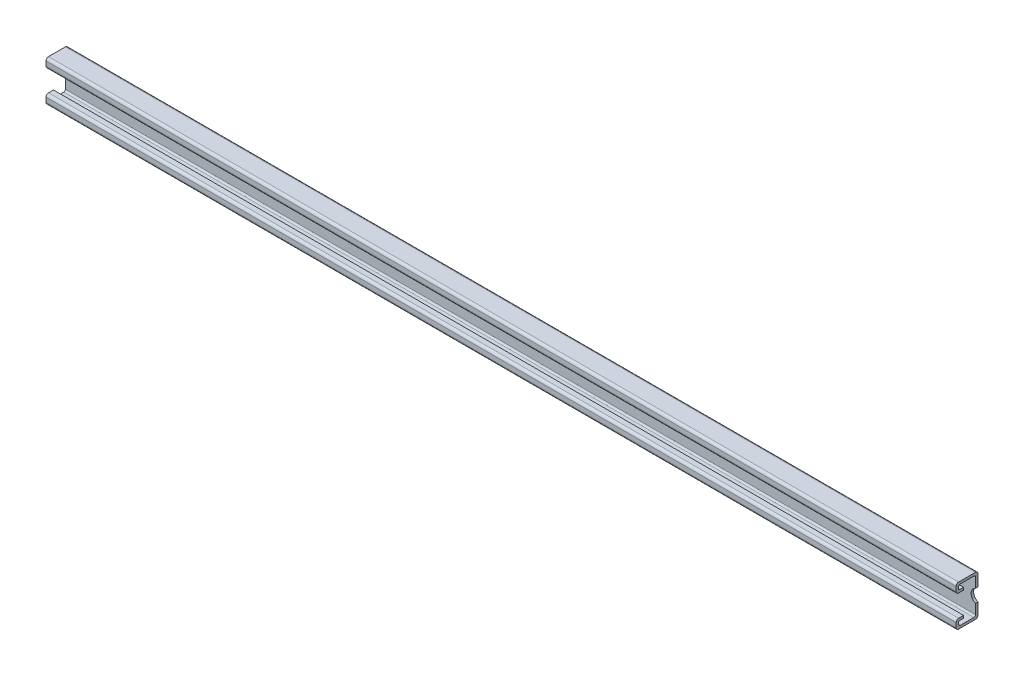
SolidWorks part; units mm, degrees
ref_plane "Front Plane" through (0, 0, 0) normal (0, 0, 1) x (1, 0, 0)
ref_plane "Top Plane" through (0, 0, 0) normal (0, 1, 0) x (1, 0, 0)
ref_plane "Right Plane" through (0, 0, 0) normal (1, 0, 0) x (0, 0, -1)
ref_plane "Plane1" through (0, 0, -11) normal (0, 0, -1) x (-1, 0, 0)
sketch "Sketch1" plane through (0, 0, -11) normal (0, 0, -1) x (-1, 0, 0)
  line L0 (0, 0) -> (0, 41)
  line L1 (0, 41) -> (-1000, 41)
  line L2 (-1000, 41) -> (-1000, 0)
  line L3 (-1000, 0) -> (0, 0)
extrude "Boss-Extrude1" add sketch "Sketch1" against normal blind 22
sketch "Sketch2" plane through (1000, 0, 0) normal (1, 0, 0) x (0, 0, -1)
  line L0 (-11, 9.5) -> (-3.5, 9.5)
  line L1 (-3.5, 9.5) -> (-3.5, 7)
  line L2 (-3.5, 7) -> (-8.5, 7)
  line L3 (-8.5, 7) -> (-8.5, 2.5)
  line L4 (-8.5, 2.5) -> (8.5, 2.5)
  line L5 (8.5, 2.5) -> (8.5, 38.5)
  line L6 (8.5, 38.5) -> (-8.5, 38.5)
  line L7 (-8.5, 38.5) -> (-8.5, 31.5)
  line L8 (-8.5, 31.5) -> (-11, 31.5)
  line L9 (-11, 31.5) -> (-11, 9.5)
extrude "Cut-Extrude1" cut sketch "Sketch2" against normal through all
sketch "Sketch3" plane through (0, 0, 8.5) normal (0, 0, -1) x (-1, 0, 0)
  line L0 (0, 34) -> (0, 31.5)
  line L1 (0, 31.5) -> (-1000, 31.5)
  line L2 (-1000, 31.5) -> (-1000, 34)
  line L3 (-1000, 34) -> (0, 34)
extrude "Boss-Extrude2" add sketch "Sketch3" along normal blind 5
sketch "Sketch4" plane through (0, 0, -11) normal (0, 0, -1) x (-1, 0, 0)
  line L0 (-117, 27.5) -> (-133, 27.5)
  line L1 (-133, 13.5) -> (-117, 13.5)
  arc A0 (-133, 27.5) -> (-133, 13.5) centre (-133, 20.5) ccw
  arc A1 (-117, 13.5) -> (-117, 27.5) centre (-117, 20.5) ccw
extrude "Cut-Extrude2" cut sketch "Sketch4" against normal through all
sketch "Sketch5" plane through (0, 0, -11) normal (0, 0, -1) x (-1, 0, 0)
  line L0 (-217, 27.5) -> (-233, 27.5)
  line L1 (-233, 13.5) -> (-217, 13.5)
  arc A0 (-233, 27.5) -> (-233, 13.5) centre (-233, 20.5) ccw
  arc A1 (-217, 13.5) -> (-217, 27.5) centre (-217, 20.5) ccw
extrude "Cut-Extrude3" cut sketch "Sketch5" against normal through all
sketch "Sketch6" plane through (0, 0, -11) normal (0, 0, -1) x (-1, 0, 0)
  line L0 (-317, 27.5) -> (-333, 27.5)
  line L1 (-333, 13.5) -> (-317, 13.5)
  arc A0 (-333, 27.5) -> (-333, 13.5) centre (-333, 20.5) ccw
  arc A1 (-317, 13.5) -> (-317, 27.5) centre (-317, 20.5) ccw
extrude "Cut-Extrude4" cut sketch "Sketch6" against normal through all
sketch "Sketch7" plane through (0, 0, -11) normal (0, 0, -1) x (-1, 0, 0)
  line L0 (-417, 27.5) -> (-433, 27.5)
  line L1 (-433, 13.5) -> (-417, 13.5)
  arc A0 (-433, 27.5) -> (-433, 13.5) centre (-433, 20.5) ccw
  arc A1 (-417, 13.5) -> (-417, 27.5) centre (-417, 20.5) ccw
extrude "Cut-Extrude5" cut sketch "Sketch7" against normal through all
sketch "Sketch8" plane through (0, 0, -11) normal (0, 0, -1) x (-1, 0, 0)
  line L0 (-517, 27.5) -> (-533, 27.5)
  line L1 (-533, 13.5) -> (-517, 13.5)
  arc A0 (-533, 27.5) -> (-533, 13.5) centre (-533, 20.5) ccw
  arc A1 (-517, 13.5) -> (-517, 27.5) centre (-517, 20.5) ccw
extrude "Cut-Extrude6" cut sketch "Sketch8" against normal through all
sketch "Sketch9" plane through (0, 0, -11) normal (0, 0, -1) x (-1, 0, 0)
  line L0 (-617, 27.5) -> (-633, 27.5)
  line L1 (-633, 13.5) -> (-617, 13.5)
  arc A0 (-633, 27.5) -> (-633, 13.5) centre (-633, 20.5) ccw
  arc A1 (-617, 13.5) -> (-617, 27.5) centre (-617, 20.5) ccw
extrude "Cut-Extrude7" cut sketch "Sketch9" against normal through all
sketch "Sketch10" plane through (0, 0, -11) normal (0, 0, -1) x (-1, 0, 0)
  line L0 (-717, 27.5) -> (-733, 27.5)
  line L1 (-733, 13.5) -> (-717, 13.5)
  arc A0 (-733, 27.5) -> (-733, 13.5) centre (-733, 20.5) ccw
  arc A1 (-717, 13.5) -> (-717, 27.5) centre (-717, 20.5) ccw
extrude "Cut-Extrude8" cut sketch "Sketch10" against normal through all
sketch "Sketch11" plane through (0, 0, -11) normal (0, 0, -1) x (-1, 0, 0)
  line L0 (-817, 27.5) -> (-833, 27.5)
  line L1 (-833, 13.5) -> (-817, 13.5)
  arc A0 (-833, 27.5) -> (-833, 13.5) centre (-833, 20.5) ccw
  arc A1 (-817, 13.5) -> (-817, 27.5) centre (-817, 20.5) ccw
extrude "Cut-Extrude9" cut sketch "Sketch11" against normal through all
sketch "Sketch12" plane through (0, 0, -11) normal (0, 0, -1) x (-1, 0, 0)
  line L0 (-917, 27.5) -> (-933, 27.5)
  line L1 (-933, 13.5) -> (-917, 13.5)
  arc A0 (-933, 27.5) -> (-933, 13.5) centre (-933, 20.5) ccw
  arc A1 (-917, 13.5) -> (-917, 27.5) centre (-917, 20.5) ccw
extrude "Cut-Extrude10" cut sketch "Sketch12" against normal through all
sketch "Sketch13" plane through (0, 0, -11) normal (0, 0, -1) x (-1, 0, 0)
  line L0 (-17, 27.5) -> (-33, 27.5)
  line L1 (-33, 13.5) -> (-17, 13.5)
  arc A0 (-33, 27.5) -> (-33, 13.5) centre (-33, 20.5) ccw
  arc A1 (-17, 13.5) -> (-17, 27.5) centre (-17, 20.5) ccw
extrude "Cut-Extrude11" cut sketch "Sketch13" against normal through all
sketch "Sketch14" plane through (0, 0, -11) normal (0, 0, -1) x (-1, 0, 0)
  line L0 (-967, 27.5) -> (-983, 27.5)
  line L1 (-983, 13.5) -> (-967, 13.5)
  arc A0 (-983, 27.5) -> (-983, 13.5) centre (-983, 20.5) ccw
  arc A1 (-967, 13.5) -> (-967, 27.5) centre (-967, 20.5) ccw
extrude "Cut-Extrude12" cut sketch "Sketch14" against normal through all
sketch "Sketch15" plane through (0, 0, -11) normal (0, 0, -1) x (-1, 0, 0)
  line L0 (-867, 27.5) -> (-883, 27.5)
  line L1 (-883, 13.5) -> (-867, 13.5)
  arc A0 (-883, 27.5) -> (-883, 13.5) centre (-883, 20.5) ccw
  arc A1 (-867, 13.5) -> (-867, 27.5) centre (-867, 20.5) ccw
extrude "Cut-Extrude13" cut sketch "Sketch15" against normal through all
sketch "Sketch16" plane through (0, 0, -11) normal (0, 0, -1) x (-1, 0, 0)
  line L0 (-767, 27.5) -> (-783, 27.5)
  line L1 (-783, 13.5) -> (-767, 13.5)
  arc A0 (-783, 27.5) -> (-783, 13.5) centre (-783, 20.5) ccw
  arc A1 (-767, 13.5) -> (-767, 27.5) centre (-767, 20.5) ccw
extrude "Cut-Extrude14" cut sketch "Sketch16" against normal through all
sketch "Sketch17" plane through (0, 0, -11) normal (0, 0, -1) x (-1, 0, 0)
  line L0 (-667, 27.5) -> (-683, 27.5)
  line L1 (-683, 13.5) -> (-667, 13.5)
  arc A0 (-683, 27.5) -> (-683, 13.5) centre (-683, 20.5) ccw
  arc A1 (-667, 13.5) -> (-667, 27.5) centre (-667, 20.5) ccw
extrude "Cut-Extrude15" cut sketch "Sketch17" against normal through all
sketch "Sketch18" plane through (0, 0, -11) normal (0, 0, -1) x (-1, 0, 0)
  line L0 (-567, 27.5) -> (-583, 27.5)
  line L1 (-583, 13.5) -> (-567, 13.5)
  arc A0 (-583, 27.5) -> (-583, 13.5) centre (-583, 20.5) ccw
  arc A1 (-567, 13.5) -> (-567, 27.5) centre (-567, 20.5) ccw
extrude "Cut-Extrude16" cut sketch "Sketch18" against normal through all
sketch "Sketch19" plane through (0, 0, -11) normal (0, 0, -1) x (-1, 0, 0)
  line L0 (-467, 27.5) -> (-483, 27.5)
  line L1 (-483, 13.5) -> (-467, 13.5)
  arc A0 (-483, 27.5) -> (-483, 13.5) centre (-483, 20.5) ccw
  arc A1 (-467, 13.5) -> (-467, 27.5) centre (-467, 20.5) ccw
extrude "Cut-Extrude17" cut sketch "Sketch19" against normal through all
sketch "Sketch20" plane through (0, 0, -11) normal (0, 0, -1) x (-1, 0, 0)
  line L0 (-367, 27.5) -> (-383, 27.5)
  line L1 (-383, 13.5) -> (-367, 13.5)
  arc A0 (-383, 27.5) -> (-383, 13.5) centre (-383, 20.5) ccw
  arc A1 (-367, 13.5) -> (-367, 27.5) centre (-367, 20.5) ccw
extrude "Cut-Extrude18" cut sketch "Sketch20" against normal through all
sketch "Sketch21" plane through (0, 0, -11) normal (0, 0, -1) x (-1, 0, 0)
  line L0 (-267, 27.5) -> (-283, 27.5)
  line L1 (-283, 13.5) -> (-267, 13.5)
  arc A0 (-283, 27.5) -> (-283, 13.5) centre (-283, 20.5) ccw
  arc A1 (-267, 13.5) -> (-267, 27.5) centre (-267, 20.5) ccw
extrude "Cut-Extrude19" cut sketch "Sketch21" against normal through all
sketch "Sketch22" plane through (0, 0, -11) normal (0, 0, -1) x (-1, 0, 0)
  line L0 (-167, 27.5) -> (-183, 27.5)
  line L1 (-183, 13.5) -> (-167, 13.5)
  arc A0 (-183, 27.5) -> (-183, 13.5) centre (-183, 20.5) ccw
  arc A1 (-167, 13.5) -> (-167, 27.5) centre (-167, 20.5) ccw
extrude "Cut-Extrude20" cut sketch "Sketch22" against normal through all
sketch "Sketch23" plane through (0, 0, -11) normal (0, 0, -1) x (-1, 0, 0)
  line L0 (-67, 27.5) -> (-83, 27.5)
  line L1 (-83, 13.5) -> (-67, 13.5)
  arc A0 (-83, 27.5) -> (-83, 13.5) centre (-83, 20.5) ccw
  arc A1 (-67, 13.5) -> (-67, 27.5) centre (-67, 20.5) ccw
extrude "Cut-Extrude21" cut sketch "Sketch23" against normal through all
fillet "Fillet1" radius 1.2 2 edges at (500, 7, 8.5) (500, 34, 8.5)
fillet "Fillet2" radius 1.6 4 edges at (500, 2.5, -8.5) (500, 38.5, 8.5) (500, 38.5, -8.5) (500, 2.5, 8.5)
fillet "Fillet3" radius 2.5 6 edges at (500, 0, -11) (500, 31.5, 11) (500, 9.5, 11) (500, 41, 11) (500, 41, -11) (500, 0, 11)
sketch "Sketch24" plane through (0, 41, 0) normal (0, 1, 0) x (1, 0, 0)
  line L0 (1000, -11) -> (0, -11) construction
  line L1 (1000, 11) -> (914.4, 11)
  line L2 (1000, 11) -> (1000, -11)
  line L3 (1000, -11) -> (914.4, -11)
  line L4 (914.4, 11) -> (914.4, -11)
  line L5 (0, -8.5) -> (0, 8.5) construction
  dimension "D1" = 914.4
extrude "Cut-Extrude22" cut sketch "Sketch24" against normal through all
